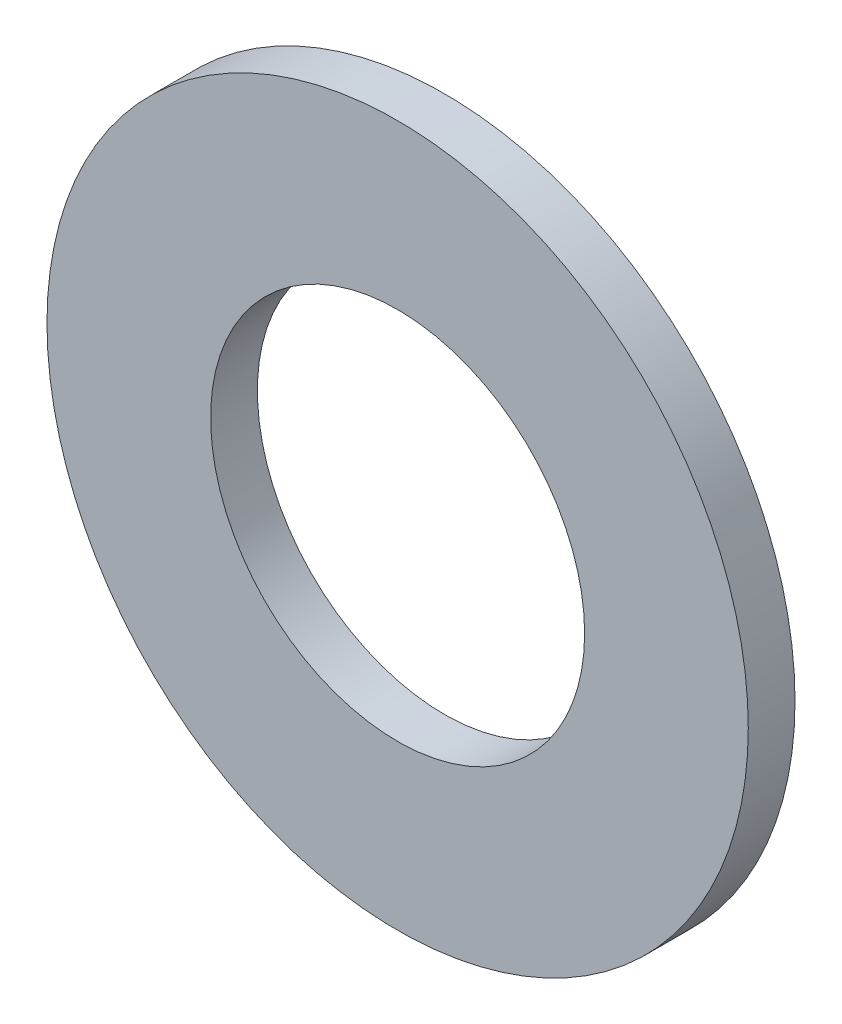
SolidWorks part; units mm, degrees
ref_plane "Plan de face" through (0, 0, 0) normal (0, 0, 1) x (1, 0, 0)
ref_plane "Plan de dessus" through (0, 0, 0) normal (0, 1, 0) x (1, 0, 0)
ref_plane "Plan de droite" through (0, 0, 0) normal (1, 0, 0) x (0, 0, -1)
sketch "Esquisse1" plane through (0, 0, 0) normal (0, 0, 1) x (1, 0, 0)
  circle A0 centre (0, 0) radius 3
  circle A1 centre (0, 0) radius 1.6
  dimension "D1" = 6
  dimension "D2" = 3.2
extrude "Extrusion1" add sketch "Esquisse1" along normal blind 0.4
